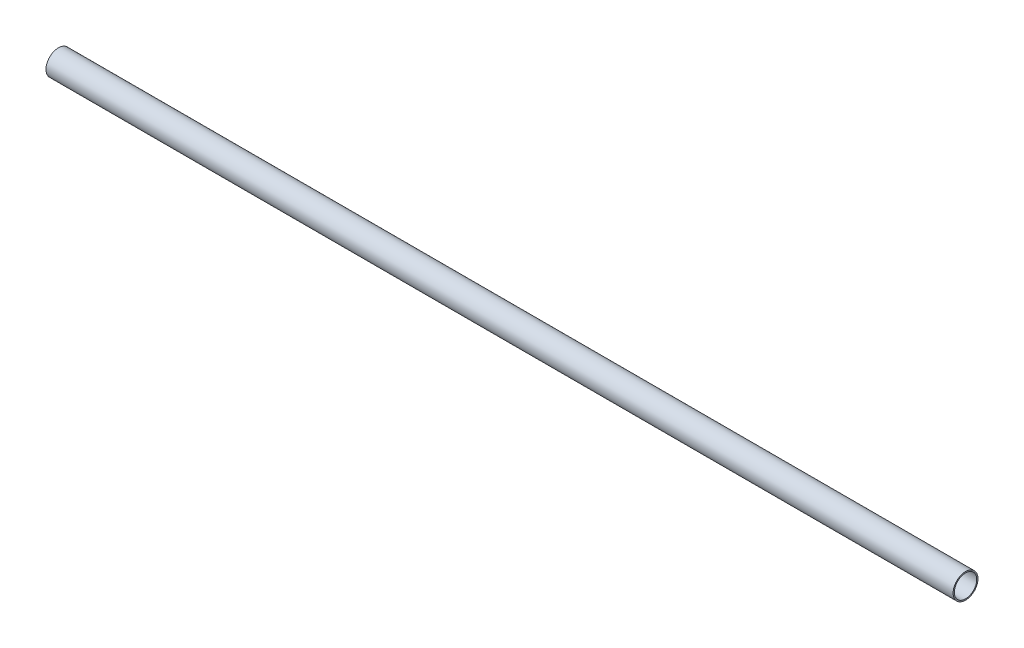
SolidWorks part; units mm, degrees
ref_plane "Front Plane" through (0, 0, 0) normal (0, 0, 1) x (1, 0, 0)
ref_plane "Top Plane" through (0, 0, 0) normal (0, 1, 0) x (1, 0, 0)
ref_plane "Right Plane" through (0, 0, 0) normal (1, 0, 0) x (0, 0, -1)
sketch "Sketch1" plane through (0, 0, 0) normal (1, 0, 0) x (0, 0, -1)
  circle A0 centre (0, 0) radius 10
  circle A1 centre (0, 0) radius 9
extrude "Boss-Extrude1" add sketch "Sketch1" along normal blind 729
